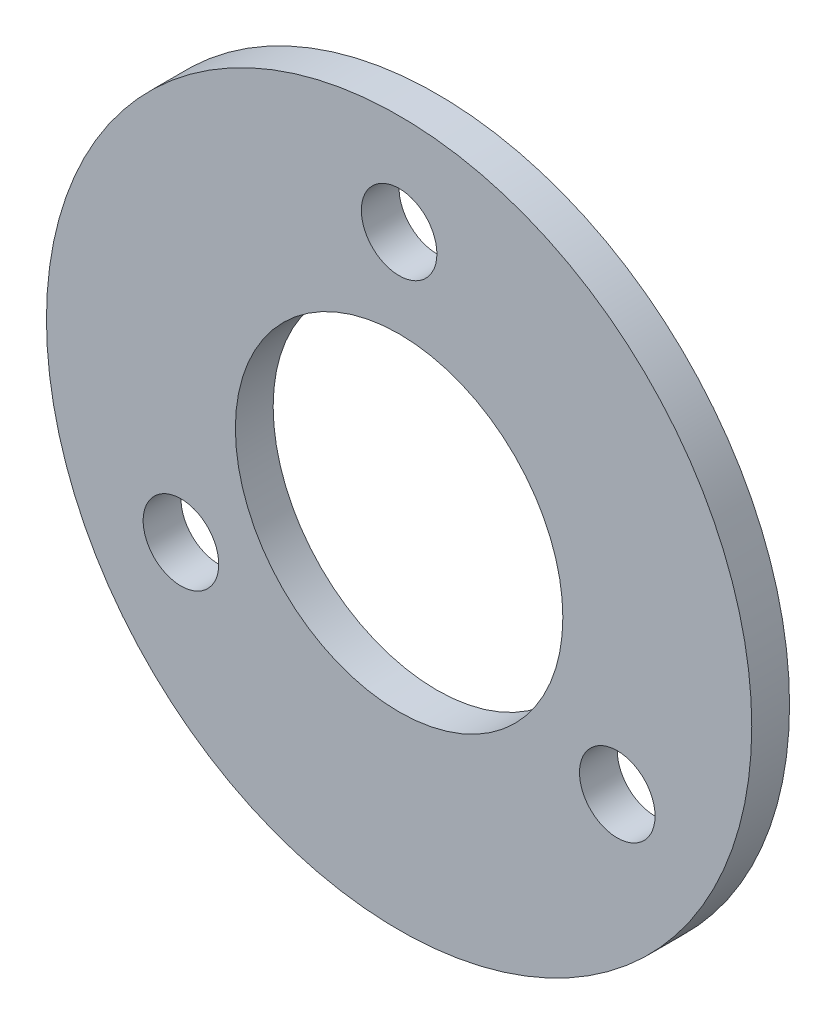
SolidWorks part; units mm, degrees
ref_plane "Plano frontal" through (0, 0, 0) normal (0, 0, 1) x (1, 0, 0)
ref_plane "Plano superior" through (0, 0, 0) normal (0, 1, 0) x (1, 0, 0)
ref_plane "Plano direito" through (0, 0, 0) normal (1, 0, 0) x (0, 0, -1)
sketch "Esboço1" plane through (0, 0, 0) normal (0, 0, 1) x (1, 0, 0)
  line L0 (0, 0) -> (0, 10) construction
  line L1 (0, 0) -> (-8.6603, -5) construction
  line L2 (0, 0) -> (8.6603, -5) construction
  circle A0 centre (0, 0) radius 14
  circle A1 centre (-8.6603, -5) radius 1.5
  circle A2 centre (8.6603, -5) radius 1.5
  circle A3 centre (0, 10) radius 1.5
  circle A4 centre (0, 0) radius 6.5
  dimension "D1" = 28
  dimension "D5" = 3
  dimension "D6" = 13
  dimension "D2" = 120
  dimension "D3" = 120
  dimension "D4" = 10
extrude "Ressalto-extrusão1" add sketch "Esboço1" along normal blind 1.5
